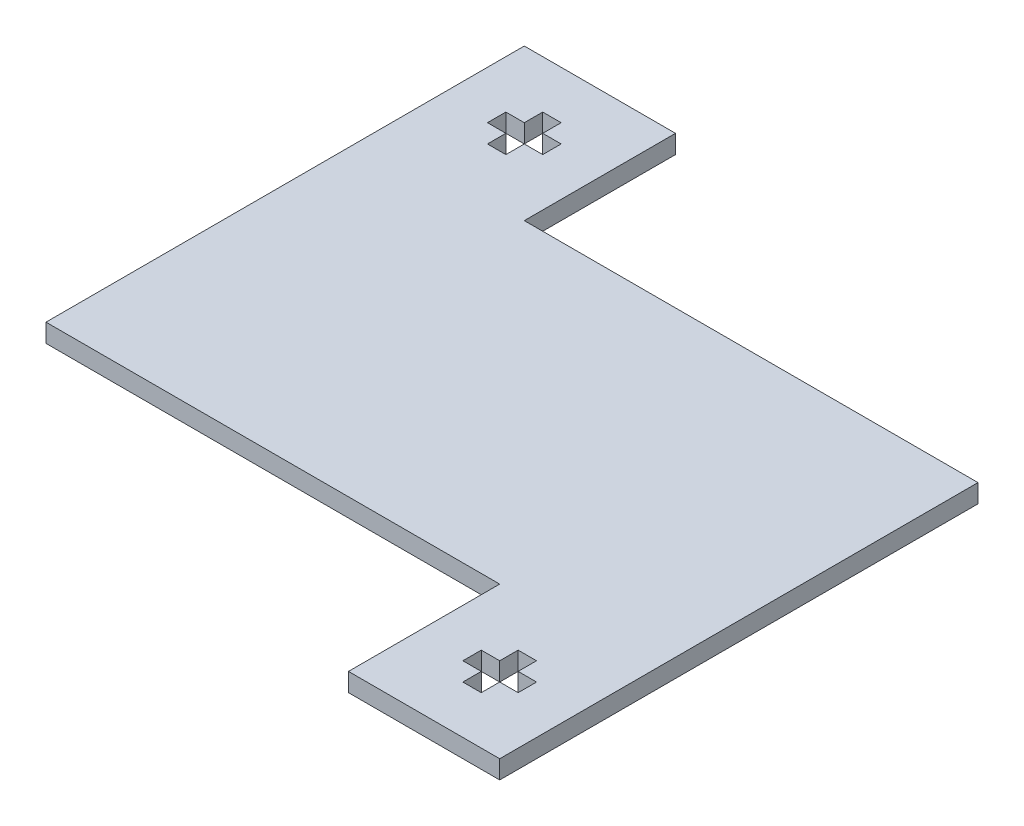
SolidWorks part; units mm, degrees
ref_plane "Front Plane" through (0, 0, 0) normal (0, 0, 1) x (1, 0, 0)
ref_plane "Top Plane" through (0, 0, 0) normal (0, 1, 0) x (1, 0, 0)
ref_plane "Right Plane" through (0, 0, 0) normal (1, 0, 0) x (0, 0, -1)
sketch "Sketch1" plane through (0, 0, 0) normal (0, 1, 0) x (1, 0, 0)
  line L0 (-78.0523, -51.526) -> (88.7089, -51.526) construction
  line L1 (-36.3633, 33.5538) -> (88.7089, 33.5538)
  line L2 (-78.0523, 33.5538) -> (-78.0523, -56.606)
  line L3 (-78.0523, -56.606) -> (47.0148, -56.606)
  line L4 (88.7089, 33.5538) -> (88.7089, -56.606)
  line L5 (-78.0523, 28.4738) -> (88.7089, 28.4738) construction
  line L6 (-36.3633, 33.5538) -> (-36.3633, -56.606) construction
  line L7 (88.7089, -11.5261) -> (-78.0523, -11.5261) construction
  line L8 (88.7089, 9.3197) -> (-78.0523, 9.3197) construction
  line L9 (5.3258, 33.5538) -> (5.3258, -56.606) construction
  line L10 (88.7089, -32.3719) -> (-78.0523, -32.3719) construction
  line L11 (-57.2078, 75.2429) -> (-57.2078, -56.606) construction
  line L12 (-78.0523, 28.4738) -> (-36.3633, 28.4738) construction
  line L13 (47.0148, 33.5538) -> (47.0148, -56.606) construction
  line L14 (-78.0523, 54.3984) -> (-36.3633, 54.3984) construction
  line L15 (-78.0523, 33.5538) -> (-78.0523, 75.2429)
  line L16 (-78.0523, 75.2429) -> (-36.3633, 75.2429)
  line L17 (67.8618, -98.295) -> (67.8618, 33.5538) construction
  line L18 (47.0148, -56.606) -> (47.0148, -98.295)
  line L19 (47.0148, -98.295) -> (88.7089, -98.295)
  line L20 (88.7089, -56.606) -> (88.7089, -98.295)
  line L21 (-36.3633, 33.5538) -> (-36.3633, 75.2429)
  line L22 (47.0148, -77.4505) -> (88.7089, -77.4505) construction
  line L23 (-57.2078, 62.0184) -> (-54.6678, 62.0184)
  line L24 (-54.6678, 62.0184) -> (-54.6678, 56.9384)
  line L25 (-54.6678, 56.9384) -> (-49.5878, 56.9384)
  line L26 (-49.5878, 56.9384) -> (-49.5878, 54.3984)
  line L27 (-49.5878, 54.3984) -> (-49.5878, 51.8584)
  line L28 (-49.5878, 51.8584) -> (-54.6678, 51.8584)
  line L29 (-54.6678, 51.8584) -> (-54.6678, 46.7784)
  line L30 (-54.6678, 46.7784) -> (-57.2078, 46.7784)
  line L31 (-57.2078, 46.7784) -> (-59.7478, 46.7784)
  line L32 (-59.7478, 46.7784) -> (-59.7478, 51.8584)
  line L33 (-59.7478, 51.8584) -> (-64.8278, 51.8584)
  line L34 (-64.8278, 51.8584) -> (-64.8278, 54.3984)
  line L35 (-64.8278, 54.3984) -> (-64.8278, 56.9384)
  line L36 (-64.8278, 56.9384) -> (-59.7478, 56.9384)
  line L37 (-59.7478, 56.9384) -> (-59.7478, 62.0184)
  line L38 (-59.7478, 62.0184) -> (-57.2078, 62.0184)
  line L39 (60.2418, -77.4505) -> (60.2418, -74.9105)
  line L40 (70.4018, -79.9905) -> (70.4018, -85.0705)
  line L41 (65.3218, -74.9105) -> (65.3218, -69.8305)
  line L42 (75.4818, -79.9905) -> (70.4018, -79.9905)
  line L43 (60.2418, -74.9105) -> (65.3218, -74.9105)
  line L44 (67.8618, -69.8305) -> (70.4018, -69.8305)
  line L45 (75.4818, -74.9105) -> (75.4818, -77.4505)
  line L46 (75.4818, -77.4505) -> (75.4818, -79.9905)
  line L47 (67.8618, -85.0705) -> (65.3218, -85.0705)
  line L48 (65.3218, -79.9905) -> (60.2418, -79.9905)
  line L49 (70.4018, -74.9105) -> (75.4818, -74.9105)
  line L50 (65.3218, -69.8305) -> (67.8618, -69.8305)
  line L51 (70.4018, -69.8305) -> (70.4018, -74.9105)
  line L52 (70.4018, -85.0705) -> (67.8618, -85.0705)
  line L53 (65.3218, -85.0705) -> (65.3218, -79.9905)
  line L54 (60.2418, -79.9905) -> (60.2418, -77.4505)
  point P33 (-57.2078, 54.3984)
  point P36 (67.8618, -77.4505)
  point P57 (-57.2078, 54.3984)
  point P68 (67.8618, -77.4505)
  dimension "D2" = 90.1598
  dimension "D3" = 41.689
  dimension "D4" = 41.689
  dimension "D5" = 41.689
  dimension "D6" = 5.08
  dimension "D7" = 5.08
  dimension "D10" = 41.689
  dimension "D11" = 41.689
  dimension "D12" = 2.54
  dimension "D13" = 2.54
  dimension "D14" = 5.08
  dimension "D15" = 5.08
  dimension "D17" = 5.08
  dimension "D18" = 5.08
  dimension "D16" = 2.54
  dimension "D8" = 20.8458
  dimension "D9" = 20.8458
extrude "Boss-Extrude1" add sketch "Sketch1" along normal blind 5.08
sketch "Sketch2" plane through (0, 5.08, 0) normal (0, 1, 0) x (1, 0, 0)
  line L0 (-36.3633, 33.5538) -> (-36.3633, -56.606) construction
  line L1 (-78.0523, -56.606) -> (47.0148, -56.606) construction
  line L2 (47.0148, -56.606) -> (47.0148, 33.5538) construction
  line L3 (88.7089, 33.5538) -> (-36.3633, 33.5538) construction
  line L4 (5.3258, 33.5538) -> (5.3258, -56.606) construction
  line L6 (-78.0523, -51.526) -> (88.7089, -51.526) construction
  line L7 (-78.0523, 75.2429) -> (-78.0523, -56.606) construction
  line L8 (88.7089, -98.295) -> (88.7089, 33.5538) construction
  line L9 (88.7089, 28.4738) -> (-78.0523, 28.4738) construction
  line L10 (-78.0523, -11.5261) -> (88.7089, -11.5261) construction
  line L11 (-78.0523, -32.3719) -> (88.7089, -32.3719) construction
  line L12 (-78.0523, 9.3197) -> (88.7089, 9.3197) construction
  dimension "D1" = 41.689
  dimension "D2" = 5.08
  dimension "D3" = 5.08
  dimension "D4" = 39.9999
  dimension "D5" = 20.8458
  dimension "D6" = 20.8458
